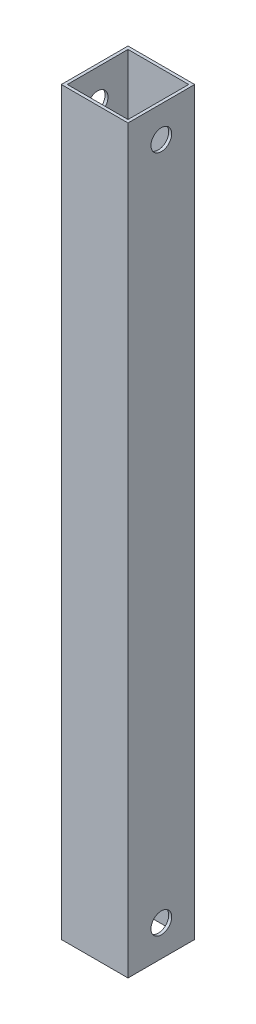
SolidWorks part; units mm, degrees
ref_plane "Alzado" through (0, 0, 0) normal (0, 0, 1) x (1, 0, 0)
ref_plane "Planta" through (0, 0, 0) normal (0, 1, 0) x (1, 0, 0)
ref_plane "Vista lateral" through (0, 0, 0) normal (1, 0, 0) x (0, 0, -1)
sketch "Croquis1" plane through (0, 0, 0) normal (0, 1, 0) x (1, 0, 0)
  line L1 (0, 0) -> (45, 0)
  line L2 (0, 0) -> (0, 45)
  line L3 (0, 45) -> (45, 45)
  line L4 (45, 0) -> (45, 45)
  dimension "D1" = 45
  dimension "D2" = 45
extrude "Saliente-Extruir1" add sketch "Croquis1" along normal blind 500
sketch "Croquis2" plane through (0, 500, 0) normal (0, 1, 0) x (1, 0, 0)
  line L0 (45, 45) -> (0, 45) construction
  line L1 (2, 43) -> (43, 43)
  line L2 (2, 43) -> (2, 2)
  line L3 (2, 2) -> (43, 2)
  line L4 (43, 43) -> (43, 2)
  line L5 (0, 0) -> (45, 0) construction
  line L6 (0, 45) -> (0, 0) construction
  line L7 (45, 0) -> (45, 45) construction
  dimension "D1" = 2
  dimension "D2" = 2
  dimension "D3" = 2
  dimension "D4" = 2
extrude "Cortar-Extruir1" cut sketch "Croquis2" against normal through all
sketch "Croquis3" plane through (45, 0, 0) normal (1, 0, 0) x (0, 0, -1)
  line L0 (0, 500) -> (45, 500) construction
  line L1 (0, 0) -> (45, 0) construction
  circle A0 centre (22.5, 479) radius 7
  circle A1 centre (22.5, 21) radius 7
  dimension "D1" = 21
  dimension "D2" = 21
extrude "Cortar-Extruir2" cut sketch "Croquis3" against normal through all
